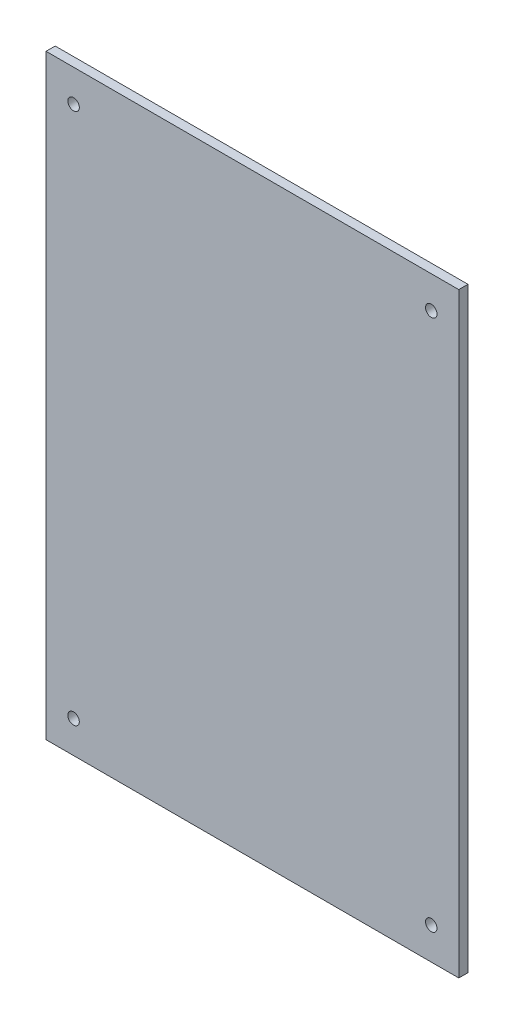
SolidWorks part; units mm, degrees
ref_plane "Front Plane" through (0, 0, 0) normal (0, 0, 1) x (1, 0, 0)
ref_plane "Top Plane" through (0, 0, 0) normal (0, 1, 0) x (1, 0, 0)
ref_plane "Right Plane" through (0, 0, 0) normal (1, 0, 0) x (0, 0, -1)
sketch "Sketch1" plane through (0, 0, 0) normal (0, 0, 1) x (1, 0, 0)
  line L1 (0, 0) -> (180, 0)
  line L2 (0, 0) -> (0, 260)
  line L3 (0, 260) -> (180, 260)
  line L4 (180, 0) -> (180, 260)
  circle A0 centre (12, 14) radius 2.5
  circle A1 centre (12, 246) radius 2.5
  circle A2 centre (168, 14) radius 2.5
  circle A3 centre (168, 246) radius 2.5
  dimension "D1" = 5
  dimension "D2" = 5
  dimension "D3" = 5
  dimension "D4" = 5
  dimension "D5" = 12
  dimension "D6" = 168
  dimension "D7" = 180
  dimension "D8" = 14
  dimension "D9" = 246
  dimension "D10" = 260
extrude "Profile" add sketch "Sketch1" along normal blind 4
equation "\"Profile_Depth\"= 4mm"
equation "\"D1@Profile\" = \"Profile_Depth\""
equation "\"Profile_Sketch_1\"= 5mm"
equation "\"D1@Sketch1\" = \"Profile_Sketch_1\""
equation "\"Profile_Sketch_2\"= 5mm"
equation "\"D2@Sketch1\" = \"Profile_Sketch_2\""
equation "\"Profile_Sketch_3\"= 5mm"
equation "\"D3@Sketch1\" = \"Profile_Sketch_3\""
equation "\"Profile_Sketch_4\"= 5mm"
equation "\"D4@Sketch1\" = \"Profile_Sketch_4\""
equation "\"Profile_Sketch_5\"= 12mm"
equation "\"D5@Sketch1\" = \"Profile_Sketch_5\""
equation "\"Profile_Sketch_6\"= 168mm"
equation "\"D6@Sketch1\" = \"Profile_Sketch_6\""
equation "\"Profile_Sketch_7\"= 180mm"
equation "\"D7@Sketch1\" = \"Profile_Sketch_7\""
equation "\"Profile_Sketch_8\"= 14mm"
equation "\"D8@Sketch1\" = \"Profile_Sketch_8\""
equation "\"Profile_Sketch_9\"= 246mm"
equation "\"D9@Sketch1\" = \"Profile_Sketch_9\""
equation "\"Profile_Sketch_10\"= 260mm"
equation "\"D10@Sketch1\" = \"Profile_Sketch_10\""
equation "\"EnvelopeWidth\"= 180mm"
equation "\"EnvelopeHeight\"= 260mm"
